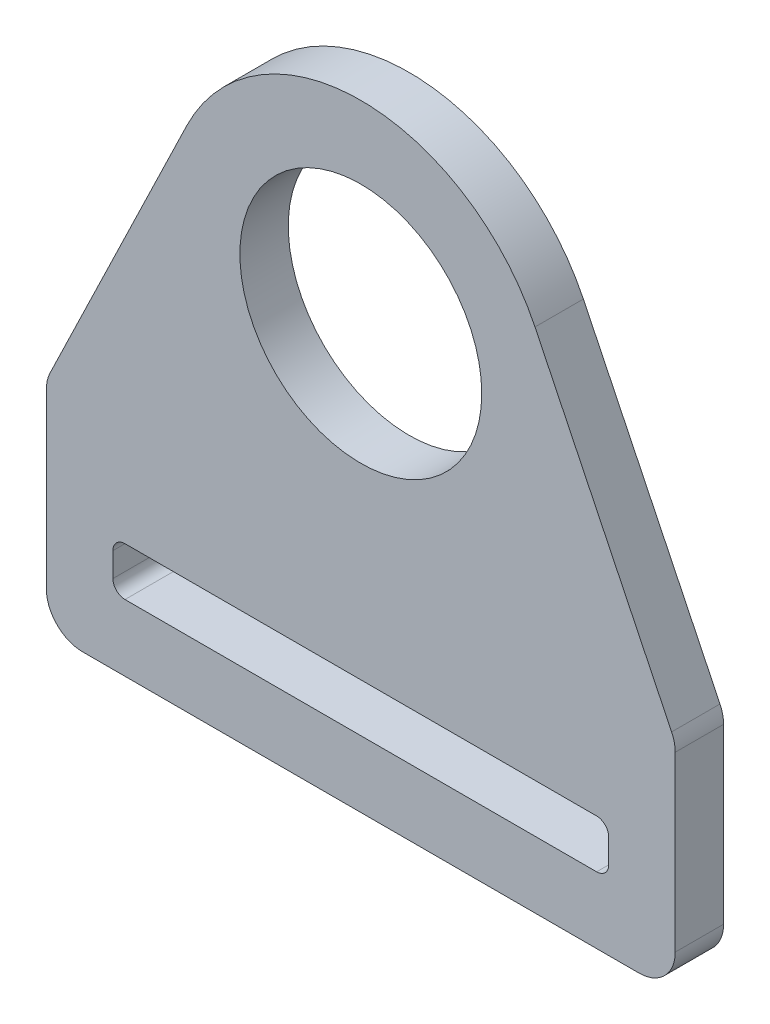
SolidWorks part; units mm, degrees
ref_plane "Спереди" through (0, 0, 0) normal (0, 0, 1) x (1, 0, 0)
ref_plane "Сверху" through (0, 0, 0) normal (0, 1, 0) x (1, 0, 0)
ref_plane "Справа" through (0, 0, 0) normal (1, 0, 0) x (0, 0, -1)
sketch "Эскиз1" plane through (0, 0, 0) normal (0, 0, 1) x (1, 0, 0)
  line L0 (0, 0) -> (0, -35)
  line L1 (-26, -35) -> (26, -35)
  line L2 (-26, -35) -> (-26, -17)
  line L3 (26, -35) -> (26, -17)
  line L4 (-26, -17) -> (-14.4027, 6.9688)
  line L5 (26, -17) -> (14.4027, 6.9688)
  line L7 (-20.5, -25.5) -> (20.5, -25.5)
  line L8 (-20.5, -25.5) -> (-20.5, -29.5)
  line L9 (-20.5, -29.5) -> (20.5, -29.5)
  line L10 (20.5, -25.5) -> (20.5, -29.5)
  line L11 (-20.5, -25.5) -> (20.5, -29.5) construction
  line L12 (-20.5, -29.5) -> (20.5, -25.5) construction
  circle A0 centre (0, 0) radius 10
  arc A1 (14.4027, 6.9688) -> (-14.4027, 6.9688) centre (0, 0) ccw
  point P3 (0, -27.5)
  dimension "D1" = 20
  dimension "D2" = 32
  dimension "D3" = 52
  dimension "D4" = 26
  dimension "D5" = 35
  dimension "D6" = 0
  dimension "D7" = 18
  dimension "D8" = 18
  dimension "D9" = 41
  dimension "D10" = 4
  dimension "D11" = 5.5
extrude "Бобышка-Вытянуть1" add sketch "Эскиз1" along normal blind 4
fillet "Скругление3" radius 3 4 edges at (-26, -17, 2) (-26, -35, 2) (26, -17, 2) (26, -35, 2)
fillet "Скругление5" radius 1 4 edges at (20.5, -29.5, 2) (20.5, -25.5, 2) (-20.5, -29.5, 2) (-20.5, -25.5, 2)
